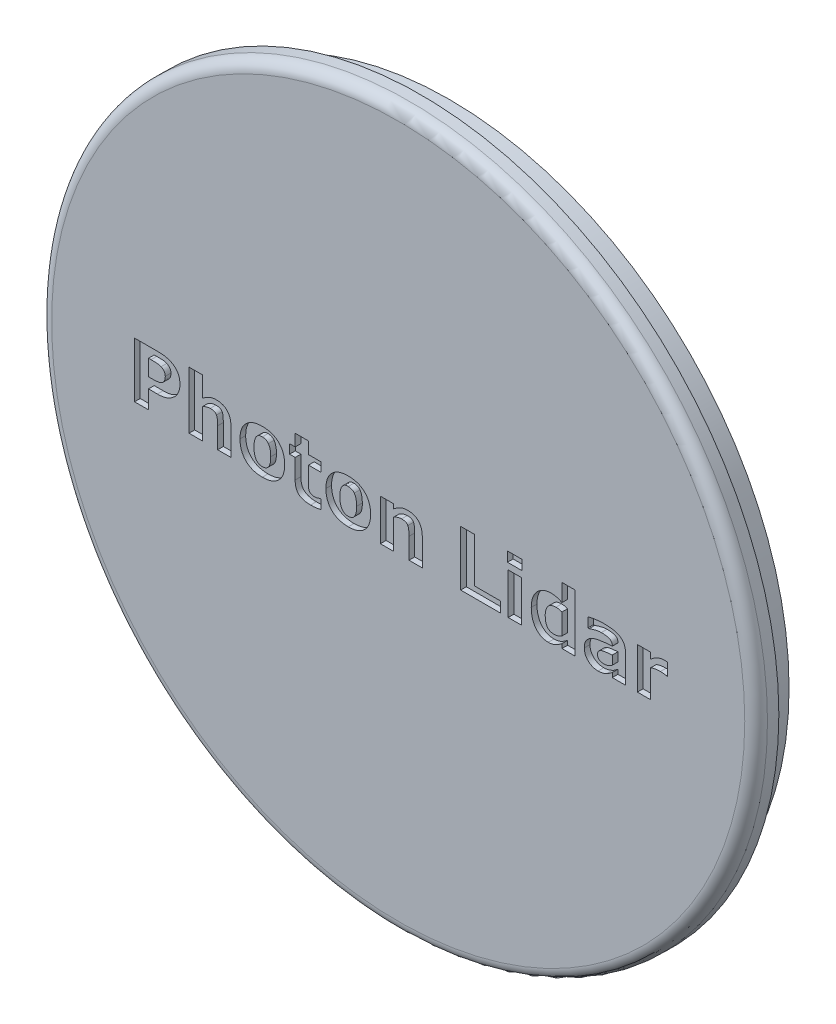
SolidWorks part; units mm, degrees
ref_plane "Plano frontal" through (0, 0, 0) normal (0, 0, 1) x (1, 0, 0)
ref_plane "Plano superior" through (0, 0, 0) normal (0, 1, 0) x (1, 0, 0)
ref_plane "Plano direito" through (0, 0, 0) normal (1, 0, 0) x (0, 0, -1)
sketch "Esboço1" plane through (0, 0, 0) normal (0, 0, 1) x (1, 0, 0)
  circle A0 centre (0, 0) radius 31.5
  dimension "D1" = 63
extrude "Ressalto-extrusão1" add sketch "Esboço1" along normal blind 2
sketch "Esboço3" plane through (0, 0, 0) normal (0, 0, -1) x (-1, 0, 0)
  circle A0 centre (0, 0) radius 29.9
  circle A1 centre (0, 0) radius 28.4
  dimension "D1" = 59.8
  dimension "D2" = 56.8
extrude "Ressalto-extrusão2" add sketch "Esboço3" along normal blind 2.5
fillet "Filete1" radius 1 1 edges at (31.5, 0, 2)
sketch "Esboço5" plane through (0, 0, 2) normal (0, 0, 1) x (1, 0, 0)
  line L0 (-34.8007, -2.5) -> (34.8007, -2.5) construction
  point P2 (0, -2.5)
  dimension "D1" = 0
  dimension "D2" = 2.5
sketch "Esboço6" plane through (0, 0, 2) normal (0, 0, 1) x (1, 0, 0)
  text T0 "Photon Lidar" font "Verdana" height in points 18
extrude "Corte-extrusão1" cut sketch "Esboço6" against normal blind 0.5
